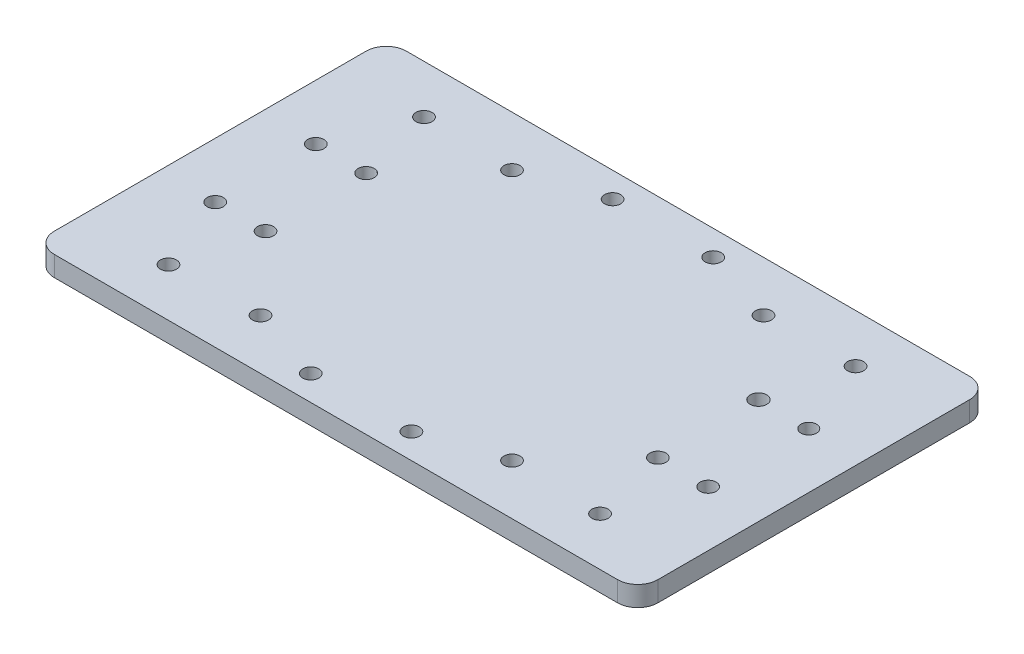
SolidWorks part; units mm, degrees
ref_plane "前视基准面" through (0, 0, 0) normal (0, 0, 1) x (1, 0, 0)
ref_plane "上视基准面" through (0, 0, 0) normal (0, 1, 0) x (1, 0, 0)
ref_plane "右视基准面" through (0, 0, 0) normal (1, 0, 0) x (0, 0, -1)
other "Configuration Table"
sketch "草图1" plane through (0, 0, 0) normal (0, 1, 0) x (1, 0, 0)
  line L1 (0, 0) -> (120, 0)
  line L2 (0, 0) -> (0, 70)
  line L3 (0, 70) -> (120, 70)
  line L4 (120, 0) -> (120, 70)
  dimension "D1" = 120
  dimension "D2" = 70
extrude "凸台-拉伸1" add sketch "草图1" along normal blind 4
sketch "草图2" plane through (0, 4, 0) normal (0, 1, 0) x (1, 0, 0)
  line L0 (0, 70) -> (0, 0) construction
  line L1 (11, 45) -> (21, 45) construction
  line L2 (11, 45) -> (11, 25) construction
  line L3 (11, 25) -> (21, 25) construction
  line L4 (21, 45) -> (21, 25) construction
  line L5 (99, 45) -> (109, 45) construction
  line L6 (99, 45) -> (99, 25) construction
  line L7 (99, 25) -> (109, 25) construction
  line L8 (109, 45) -> (109, 25) construction
  line L9 (17.1, 60.4) -> (102.9, 60.4) construction
  line L10 (17.1, 60.4) -> (17.1, 9.6) construction
  line L11 (17.1, 9.6) -> (102.9, 9.6) construction
  line L12 (102.9, 60.4) -> (102.9, 9.6) construction
  line L13 (35, 60) -> (85, 60) construction
  line L14 (35, 60) -> (35, 10) construction
  line L15 (35, 10) -> (85, 10) construction
  line L16 (85, 60) -> (85, 10) construction
  line L17 (120, 0) -> (120, 70) construction
  line L18 (11, 45) -> (11, 70) construction
  line L19 (120, 70) -> (0, 70) construction
  line L20 (11, 25) -> (11, 0) construction
  line L21 (0, 0) -> (120, 0) construction
  line L22 (109, 45) -> (109, 70) construction
  line L23 (109, 25) -> (109, 0) construction
  line L24 (35, 60) -> (35, 70) construction
  line L25 (35, 10) -> (35, 0) construction
  line L26 (17.1, 60.4) -> (17.1, 70) construction
  line L27 (17.1, 9.6) -> (17.1, 0) construction
  line L28 (35, 60) -> (0, 60) construction
  line L29 (85, 60) -> (120, 60) construction
  line L30 (17.1, 60.4) -> (0, 60.4) construction
  line L31 (102.9, 60.4) -> (120, 60.4) construction
  circle A0 centre (11, 45) radius 1.6
  circle A1 centre (21, 45) radius 1.6
  circle A2 centre (21, 25) radius 1.6
  circle A3 centre (11, 25) radius 1.6
  circle A4 centre (109, 45) radius 1.55
  circle A5 centre (99, 45) radius 1.65
  circle A6 centre (109, 25) radius 1.6
  circle A7 centre (99, 25) radius 1.6
  circle A8 centre (102.9, 9.6) radius 1.6
  circle A9 centre (17.1, 9.6) radius 1.6
  circle A10 centre (17.1, 60.4) radius 1.6
  circle A11 centre (102.9, 60.4) radius 1.6
  circle A12 centre (85, 60) radius 1.6
  circle A13 centre (85, 10) radius 1.6
  circle A14 centre (35, 10) radius 1.6
  circle A15 centre (35, 60) radius 1.6
  dimension "D1" = 3.1
  dimension "D2" = 3.2
  dimension "D3" = 3.3
  dimension "D4" = 3.2
  dimension "D5" = 3.2
  dimension "D6" = 3.2
  dimension "D7" = 3.2
  dimension "D8" = 3.2
  dimension "D9" = 3.2
  dimension "D10" = 3.2
  dimension "D11" = 3.2
  dimension "D12" = 3.2
  dimension "D13" = 3.2
  dimension "D14" = 3.2
  dimension "D15" = 3.2
  dimension "D16" = 3.2
  dimension "D17" = 10
  dimension "D18" = 20
  dimension "D19" = 10
  dimension "D20" = 20
  dimension "D21" = 11
  dimension "D22" = 11
  dimension "D23" = 85.8
  dimension "D24" = 50.8
  dimension "D26" = 50
  dimension "D27" = 50
extrude "切除-拉伸1" cut sketch "草图2" against normal blind 4
sketch "草图3" plane through (0, 4, 0) normal (0, 1, 0) x (1, 0, 0)
  line L0 (0, 0) -> (120, 0) construction
  line L1 (50, 5) -> (0, 5) construction
  line L2 (0, 70) -> (0, 0) construction
  line L3 (70, 5) -> (120, 5) construction
  line L4 (120, 0) -> (120, 70) construction
  line L5 (120, 70) -> (0, 70) construction
  line L6 (50, 65) -> (0, 65) construction
  line L7 (70, 65) -> (120, 65) construction
  circle A0 centre (50, 5) radius 1.6
  circle A1 centre (70, 5) radius 1.6
  circle A2 centre (50, 65) radius 1.6
  circle A3 centre (70, 65) radius 1.6
  dimension "D1" = 3.2
  dimension "D2" = 3.2
  dimension "D6" = 3.2
  dimension "D7" = 3.2
  dimension "D3" = 20
  dimension "D4" = 5
  dimension "D5" = 5
  dimension "D8" = 20
  dimension "D9" = 5
  dimension "D10" = 5
extrude "切除-拉伸2" cut sketch "草图3" against normal blind 4
fillet "圆角1" radius 4 4 edges at (0, 2, -70) (120, 2, -70) (120, 2, 0) (0, 2, 0)
